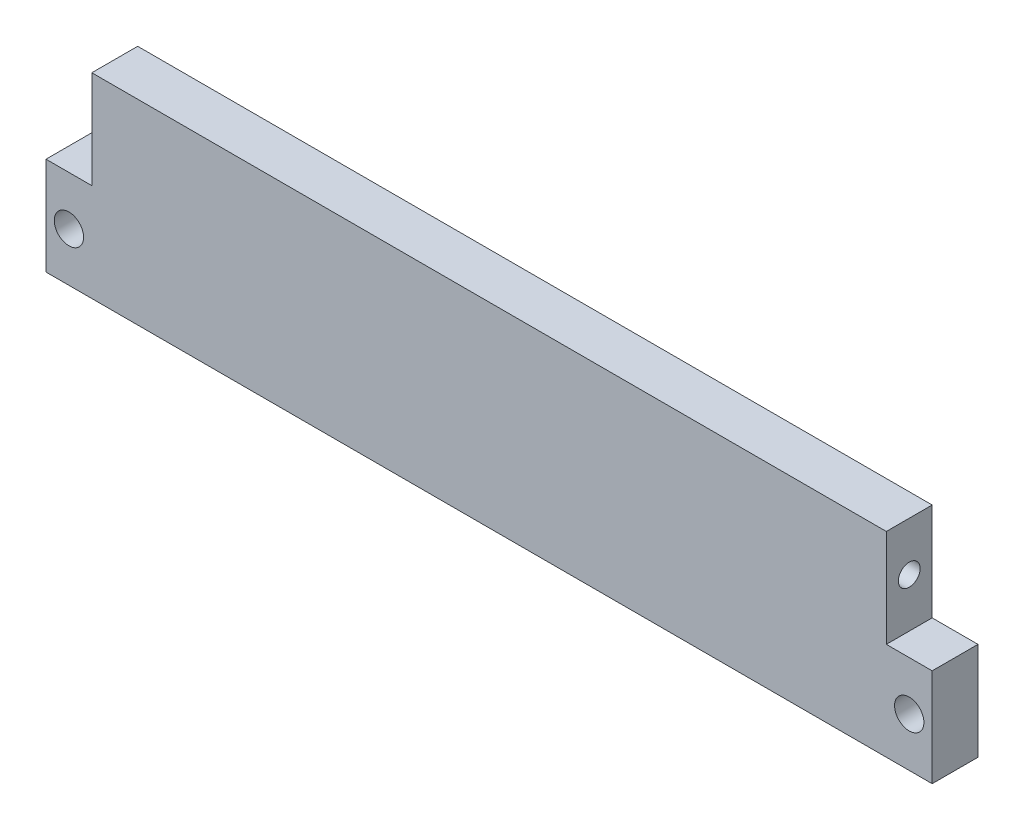
SolidWorks part; units mm, degrees
ref_plane "Front Plane" through (0, 0, 0) normal (0, 0, 1) x (1, 0, 0)
ref_plane "Top Plane" through (0, 0, 0) normal (0, 1, 0) x (1, 0, 0)
ref_plane "Right Plane" through (0, 0, 0) normal (1, 0, 0) x (0, 0, -1)
sketch "Sketch1" plane through (0, 0, 0) normal (0, 0, 1) x (1, 0, 0)
  line L0 (-46.0375, 0) -> (46.0375, 0)
  line L1 (46.0375, 0) -> (46.0375, 10.16)
  line L2 (46.0375, 10.16) -> (41.275, 10.16)
  line L3 (41.275, 10.16) -> (41.275, 20.32)
  line L4 (41.275, 20.32) -> (-41.275, 20.32)
  line L5 (-41.275, 20.32) -> (-41.275, 10.16)
  line L6 (-41.275, 10.16) -> (-46.0375, 10.16)
  line L7 (-46.0375, 10.16) -> (-46.0375, 0)
  line L8 (0, -1000) -> (0, 49000) construction
  circle A0 centre (-43.6562, 5.08) radius 1.524
  circle A1 centre (43.6562, 5.08) radius 1.524
  point P9 (0, 0)
  point P12 (-46.0375, 5.08)
  dimension "D5" = 3.048
  dimension "D1" = 92.075
  dimension "D2" = 82.55
  dimension "D3" = 20.32
  dimension "D4" = 10.16
  dimension "D6" = 2.3813
extrude "Boss-Extrude1" add sketch "Sketch1" along normal blind 4.7625
sketch "Sketch2" plane through (41.275, 0, 0) normal (1, 0, 0) x (0, 0, -1)
  line L0 (-4.7625, 20.32) -> (0, 20.32) construction
  line L1 (0, 10.16) -> (0, 20.32) construction
  circle A0 centre (-2.3813, 15.24) radius 1.1303
  dimension "D3" = 2.2606
  dimension "D1" = 5.08
  dimension "D2" = 2.3813
extrude "Cut-Extrude1" cut sketch "Sketch2" against normal blind 6.35
sketch "Sketch3" plane through (-41.275, 0, 0) normal (-1, 0, 0) x (0, 0, 1)
  line L0 (4.7625, 20.32) -> (0, 20.32) construction
  line L2 (4.7625, 20.32) -> (4.7625, 10.16) construction
  circle A0 centre (2.3813, 15.24) radius 1.1303
  point P6 (4.7625, 15.7558)
  dimension "D3" = 2.2606
  dimension "D1" = 5.08
  dimension "D2" = 2.3813
extrude "Cut-Extrude2" cut sketch "Sketch3" against normal blind 6.35
